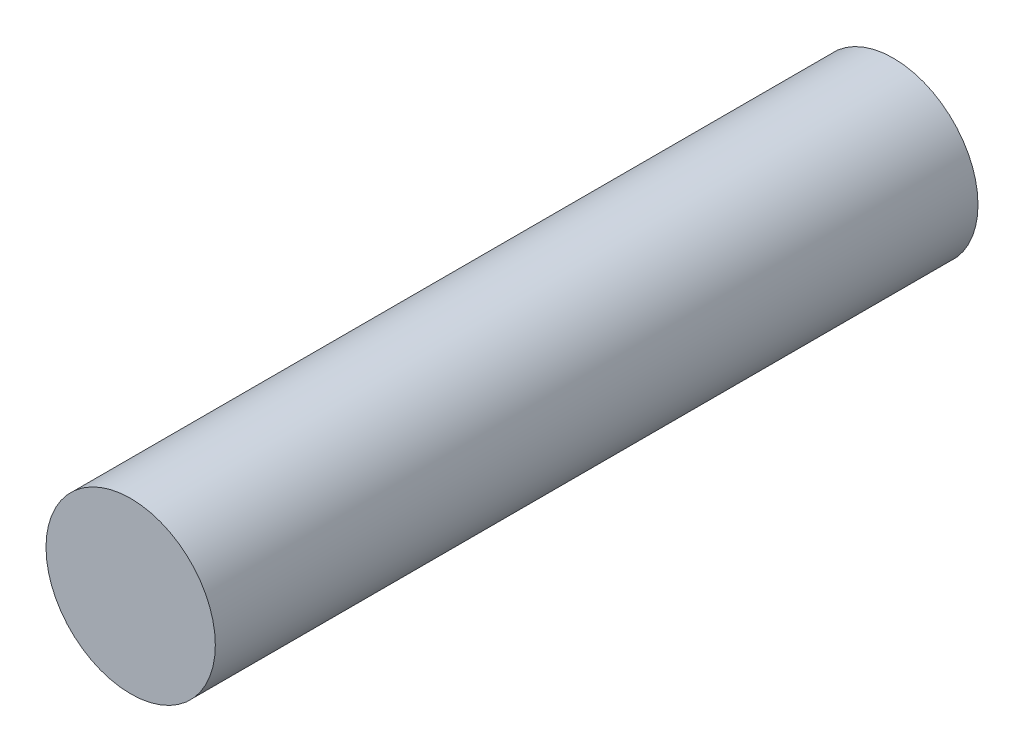
SolidWorks part; units mm, degrees
ref_plane "Front" through (0, 0, 0) normal (0, 0, 1) x (1, 0, 0)
ref_plane "Top" through (0, 0, 0) normal (0, 1, 0) x (1, 0, 0)
ref_plane "Right" through (0, 0, 0) normal (1, 0, 0) x (0, 0, -1)
sketch "Sketch1" plane through (0, 0, 0) normal (0, 0, 1) x (1, 0, 0)
  circle A0 centre (0, 0) radius 1.5875
  dimension "D1" = 3.175
extrude "Boss-Extrude1" add sketch "Sketch1" along normal blind 14.3002
